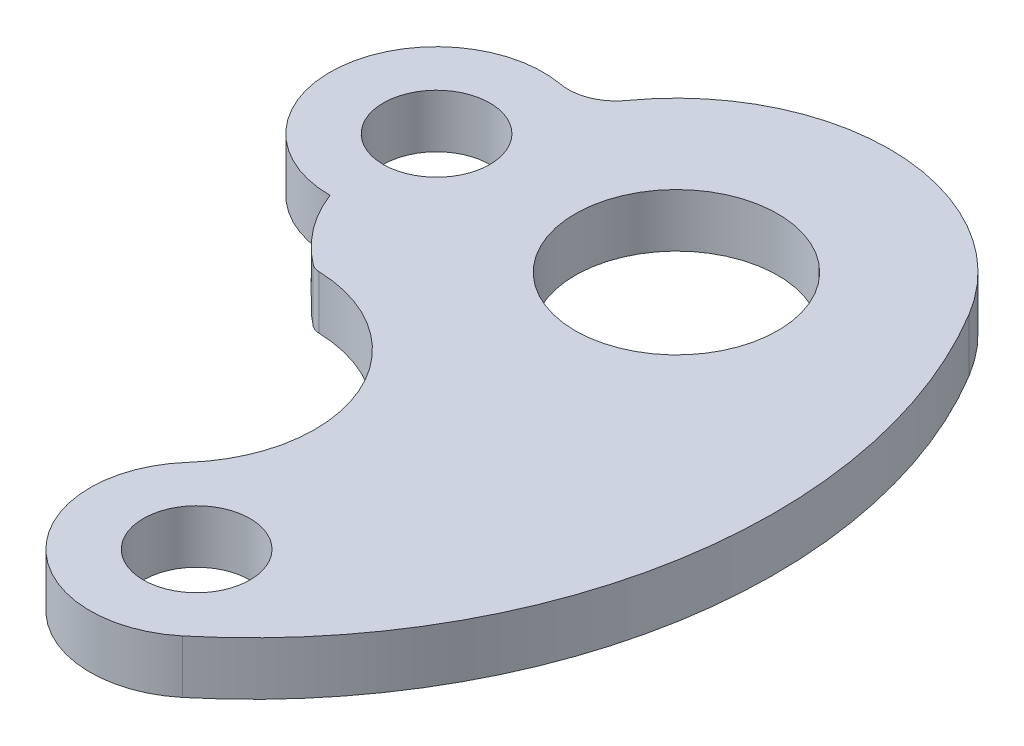
SolidWorks part; units mm, degrees
ref_plane "Front Plane" through (0, 0, 0) normal (0, 0, 1) x (1, 0, 0)
ref_plane "Top Plane" through (0, 0, 0) normal (0, 1, 0) x (1, 0, 0)
ref_plane "Right Plane" through (0, 0, 0) normal (1, 0, 0) x (0, 0, -1)
sketch "Sketch1" plane through (0, 0, 0) normal (0, 1, 0) x (1, 0, 0)
  line L0 (0, 55.349) -> (0, -90) construction
  line L1 (-45, 0) -> (140.0889, 0) construction
  line L2 (-62.8885, -8.9443) -> (-17.8885, -98.9443)
  circle A0 centre (0, 0) radius 14
  circle A1 centre (0, 0) radius 19
  circle A2 centre (-45, 0) radius 10
  circle A3 centre (0, -90) radius 10
  arc A4 (-41.4368, 19.68) -> (-45, -20) centre (-45, 0) ccw
  arc A5 (-14.943, -76.7069) -> (12.745, -105.4131) centre (0, -90) ccw
  arc A6 (34.2798, 20.613) -> (-32.517, 23.2947) centre (0, 0) ccw
  arc A7 (-41.4368, 19.68) -> (-32.517, 23.2947) centre (-39.8333, 28.536) ccw
  arc A9 (-14.943, -76.7069) -> (-33.6072, -33.4371) centre (-34.369, -59.4259) ccw
  arc A10 (-35.293, -32.8395) -> (-33.6072, -33.4371) centre (-33.5217, -30.5193) ccw
  arc A12 (12.745, -105.4131) -> (34.2798, 20.613) centre (-49.7057, -29.8889) ccw
  spline S0 degree 3 poles (-45, -20) (-42.9513, -25.1834) (-39.7156, -29.4633) (-35.293, -32.8395) knots 0 0 0 0 0.944417 0.944417 0.944417 0.944417
  dimension "D1" = 38
  dimension "D2" = 28
  dimension "D5" = 20
  dimension "D6" = 20
  dimension "D7" = 40
  dimension "D8" = 40
  dimension "D9" = 40
  dimension "D10" = 9
  dimension "D11" = 26
  dimension "D12" = 98
  dimension "D3" = 90
  dimension "D4" = 45
extrude "Boss-Extrude1" add sketch "Sketch1" along normal blind 10 contours A4 S0 A10 A9 A5 A12 A6 A7 A1 A2 A3
